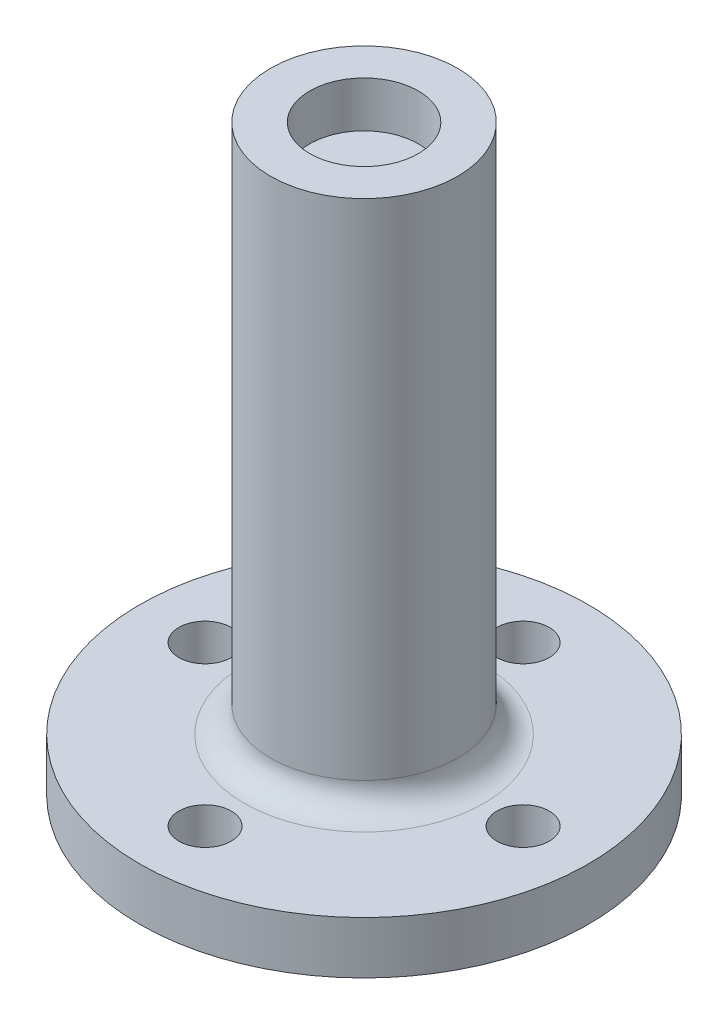
SolidWorks part; units mm, degrees
ref_plane "Front Plane" through (0, 0, 0) normal (0, 0, 1) x (1, 0, 0)
ref_plane "Top Plane" through (0, 0, 0) normal (0, 1, 0) x (1, 0, 0)
ref_plane "Right Plane" through (0, 0, 0) normal (1, 0, 0) x (0, 0, -1)
sketch "Sketch1" plane through (0, 0, 0) normal (1, 0, 0) x (0, 0, -1)
  line L0 (-7.15, 3.5) -> (-4.15, 3.5)
  line L1 (-4.15, 3.5) -> (-4.15, 0)
  line L2 (-4.15, 0) -> (0, 0)
  line L3 (0, 0) -> (0, -41)
  line L4 (0, -41) -> (-17.15, -41)
  line L5 (-17.15, -41) -> (-17.15, -37)
  line L6 (-17.15, -37) -> (-9.15, -37)
  line L7 (-7.15, -35) -> (-7.15, 3.5)
  arc A0 (-9.15, -37) -> (-7.15, -35) centre (-9.15, -35) ccw
  point P11 (-7.15, -37)
  point P12 (-2.075, 0)
  dimension "D7" = 2
  dimension "D1" = 4.15
  dimension "D2" = 3
  dimension "D3" = 4
  dimension "D4" = 10
  dimension "D6" = 41
  dimension "D5" = 3.5
revolve "Revolve1" add sketch "Sketch1" angle 360 about L3
sketch "Sketch2" plane through (0, -37, 0) normal (0, 1, 0) x (1, 0, 0)
  line L0 (0, 17.15) -> (0, 7.15) construction
  circle A0 centre (0, 0) radius 17.15 construction
  circle A1 centre (0, 0) radius 7.15 construction
  circle A2 centre (0, 12.15) radius 2
  circle A6 centre (12.15, 0) radius 2
  circle A7 centre (0, -12.15) radius 2
  circle A8 centre (-12.15, 0) radius 2
  point P18 (-0.5, 0.5)
  point P19 (0, 0)
  dimension "D1" = 4
  dimension "D2" = 4
extrude "Cut-Extrude1" cut sketch "Sketch2" against normal up to surface (4 mm away) up to face at (0, -41, 17.15)
equation "\"D1@Sketch1\"=8.3/2"
